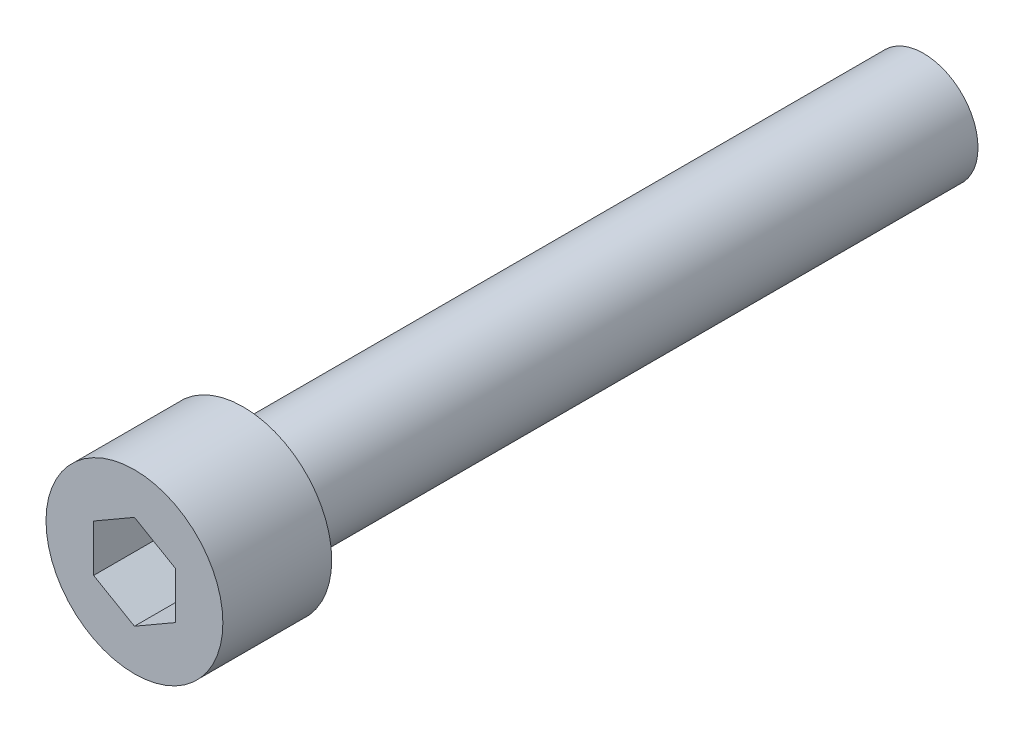
SolidWorks part; units mm, degrees
ref_plane "Płaszczyzna przednia" through (0, 0, 0) normal (0, 0, 1) x (1, 0, 0)
ref_plane "Płaszczyzna górna" through (0, 0, 0) normal (0, 1, 0) x (1, 0, 0)
ref_plane "Płaszczyzna prawa" through (0, 0, 0) normal (1, 0, 0) x (0, 0, -1)
sketch "Szkic1" plane through (0, 0, 0) normal (1, 0, 0) x (0, 0, -1)
  line L0 (0, 0) -> (30.4213, 0) construction
  line L1 (0, 0) -> (0, 6.5)
  line L2 (0, 6.5) -> (8, 6.5)
  line L3 (8, 6.5) -> (8, 4)
  line L4 (8, 4) -> (58, 4)
  line L5 (58, 4) -> (58, 0)
  line L6 (58, 0) -> (0, 0)
  dimension "D1" = 13
  dimension "D2" = 8
  dimension "D3" = 8
  dimension "D4" = 50
revolve "Obrót1" add sketch "Szkic1" angle 360 about L0
sketch "Szkic2" plane through (0, 0, 0) normal (0, 0, 1) x (1, 0, 0)
  line L1 (-3, -1.7321) -> (0, -3.4641)
  line L2 (0, -3.4641) -> (3, -1.7321)
  line L3 (3, -1.7321) -> (3, 1.7321)
  line L4 (3, 1.7321) -> (0, 3.4641)
  line L5 (0, 3.4641) -> (-3, 1.7321)
  line L6 (-3, 1.7321) -> (-3, -1.7321)
  circle A0 centre (0, 0) radius 3 construction
  dimension "D1" = 6
extrude "Wytnij-wyciągnięcie1" cut sketch "Szkic2" against normal blind 6
